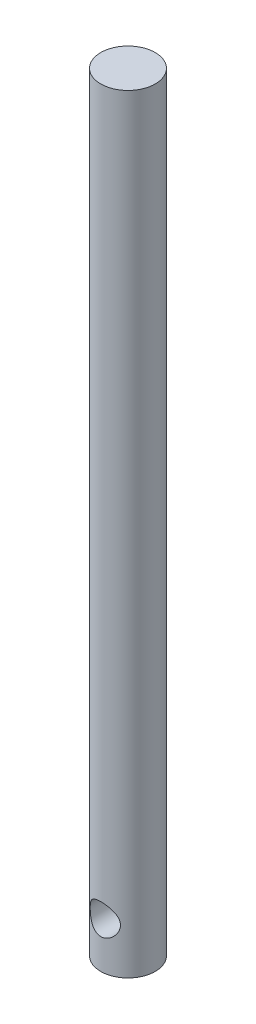
SolidWorks part; units mm, degrees
ref_plane "Front Plane" through (0, 0, 0) normal (0, 0, 1) x (1, 0, 0)
ref_plane "Top Plane" through (0, 0, 0) normal (0, 1, 0) x (1, 0, 0)
ref_plane "Right Plane" through (0, 0, 0) normal (1, 0, 0) x (0, 0, -1)
sketch "Sketch5" plane through (0, 0, 0) normal (0, 1, 0) x (1, 0, 0)
  circle A0 centre (32.6665, 0) radius 9
extrude "Boss-Extrude2" add sketch "Sketch5" along normal blind 254 separate body
ref_plane "Plane1" through (0, 0, 9) normal (0, 0, 1) x (1, 0, 0)
sketch "Sketch7" plane through (0, 0, 9) normal (0, 0, 1) x (1, 0, 0)
  line L0 (41.6665, 0) -> (23.6665, 0)
  line L1 (13.2, 0) -> (-13.2, 0) construction
  line L2 (41.6665, 0) -> (41.6665, 254) construction
  line L3 (23.6665, 254) -> (23.6665, 0) construction
  line L4 (32.6665, 0) -> (32.6665, 15) construction
  circle A0 centre (32.6665, 15) radius 5
extrude "Cut-Extrude2" cut sketch "Sketch7" against normal blind 50
